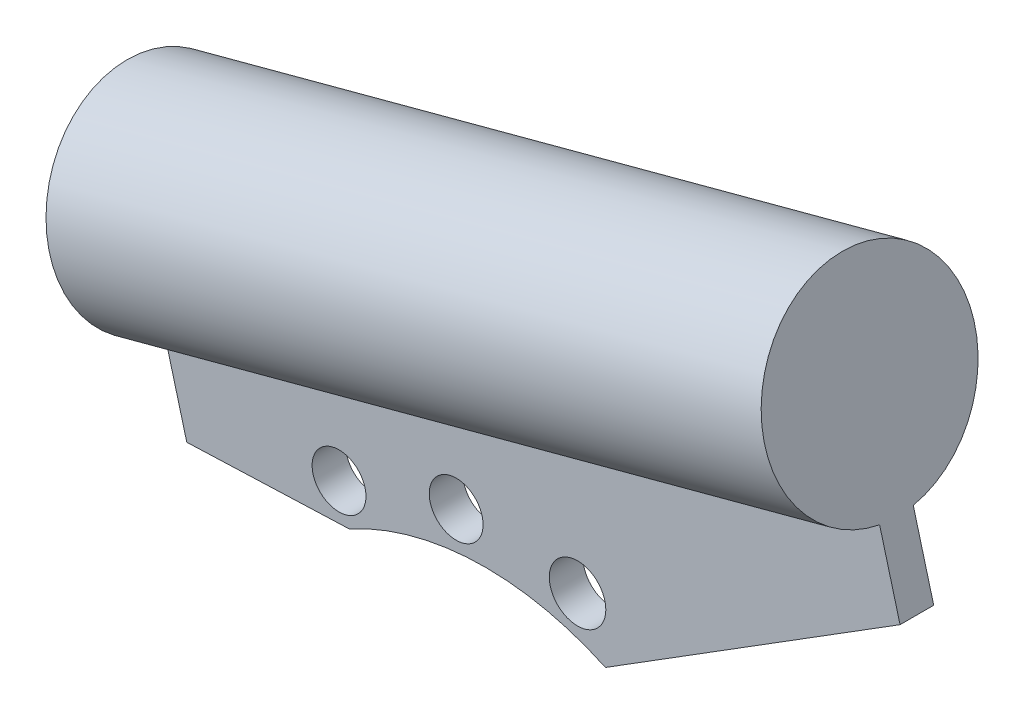
SolidWorks part; units mm, degrees
ref_plane "Front Plane" through (0, 0, 0) normal (0, 0, 1) x (1, 0, 0)
ref_plane "Top Plane" through (0, 0, 0) normal (0, 1, 0) x (1, 0, 0)
ref_plane "Right Plane" through (0, 0, 0) normal (1, 0, 0) x (0, 0, -1)
sketch "Sketch1" plane through (0, 0, 32.6705) normal (0, 0, 1) x (1, 0, 0)
  line L0 (-70.4968, 21.1178) -> (-77.0803, 45.6875)
  line L1 (-77.0803, 45.6875) -> (29.1716, 74.1576)
  line L2 (29.1716, 74.1576) -> (32.1573, 63.0146)
  line L3 (32.1573, 63.0146) -> (-11.6123, 35.6266)
  line L4 (-70.4968, 21.1178) -> (-64.2594, 21.1178)
  line L5 (-29.4571, -2.3939) -> (-82.6495, -2.3939) construction
  arc A1 (-11.6123, 35.6266) -> (-64.2594, 21.1178) centre (-29.4571, -2.3939) ccw
  circle A2 centre (-65.4335, 28.6214) radius 4
  circle A3 centre (-51.1953, 39.8399) radius 4
  circle A6 centre (-33.7914, 44.9079) radius 4
  circle A7 centre (-15.7562, 43.0872) radius 4.1989
  dimension "D3" = 42
  dimension "D1" = 110
  dimension "D2" = 75
extrude "Boss-Extrude1" add sketch "Sketch1" along normal blind 5
sketch "Sketch2" plane through (-60.495, -16.2096, 0) normal (-0.9659, -0.2588, 0) x (0, 0, 1)
  line L0 (35.1705, 38.6442) -> (35.1705, 80.1597) construction
  line L1 (37.6705, 38.6442) -> (32.6705, 38.6442) construction
  line L2 (37.6705, 64.0805) -> (32.6705, 64.0805) construction
  line L3 (37.6705, 64.0805) -> (37.6705, 64.2822)
  line L4 (32.6705, 64.0805) -> (32.6705, 64.2822)
  line L5 (32.6705, 64.0805) -> (37.6705, 64.0805)
  arc A0 (37.6705, 64.2822) -> (32.6705, 64.2822) centre (35.1705, 79.6805) ccw
  circle A1 centre (35.1705, 79.6805) radius 13.5
  dimension "D1" = 31.2
  dimension "D2" = 27
extrude "Boss-Extrude2" add sketch "Sketch2" against normal blind 106
sketch "Sketch3" plane through (41.8931, 11.2252, 0) normal (0.9659, 0.2588, 0) x (0, 0, -1)
  line L0 (-37.6705, 64.2822) -> (-37.6705, 64.0805)
  line L1 (-37.6705, 64.0805) -> (-32.6705, 64.0805)
  line L2 (-32.6705, 64.0805) -> (-32.6705, 64.2822)
  arc A0 (-32.6705, 64.2822) -> (-37.6705, 64.2822) centre (-35.1705, 79.6805) ccw
extrude "Boss-Extrude4" add sketch "Sketch3" along normal up to vertex (4 mm away)
sketch "Sketch4" plane through (0, 0, 37.6705) normal (0, 0, 1) x (1, 0, 0)
  line L0 (-73.8146, 33.5) -> (-49.6752, 34.4195)
  line L1 (-77.1324, 45.8822) -> (-70.4968, 21.1178) construction
  line L2 (-73.8146, 33.5) -> (-70.4968, 21.1178)
  line L3 (-70.4968, 21.1178) -> (-64.2594, 21.1178)
  arc A0 (-11.6123, 35.6266) -> (-64.2594, 21.1178) centre (-29.4571, -2.3939) ccw construction
  arc A1 (-49.6752, 34.4195) -> (-64.2594, 21.1178) centre (-29.4571, -2.3939) ccw
extrude "Cut-Extrude1" cut sketch "Sketch4" against normal blind 10
